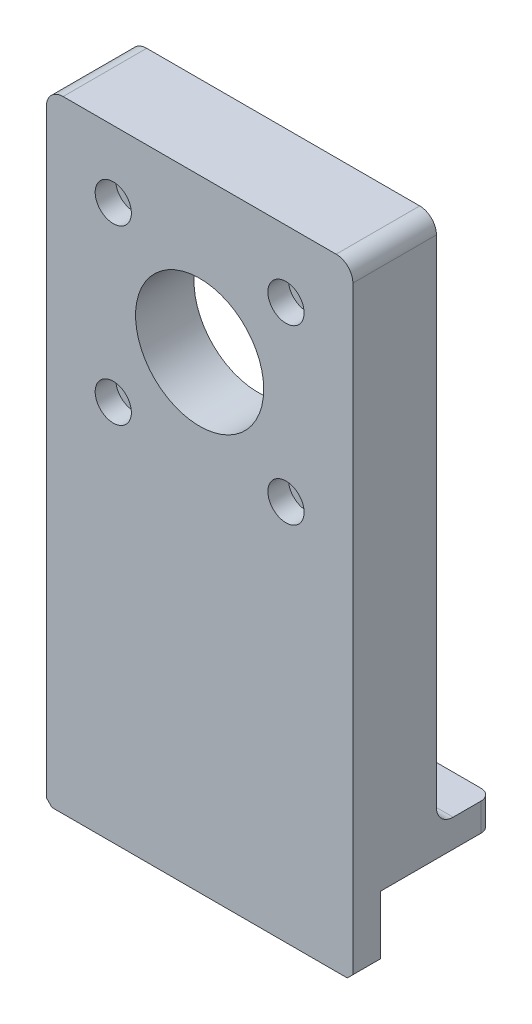
SolidWorks part; units mm, degrees
ref_plane "Přední rovina" through (0, 0, 0) normal (0, 0, 1) x (1, 0, 0)
ref_plane "Horní rovina" through (0, 0, 0) normal (0, 1, 0) x (1, 0, 0)
ref_plane "Pravá rovina" through (0, 0, 0) normal (1, 0, 0) x (0, 0, -1)
sketch "Skica2" plane through (0, 0, 0) normal (0, 0, 1) x (1, 0, 0)
  line L0 (-27.5, 24.5) -> (-27.5, -72.5)
  line L1 (27.5, 24.5) -> (27.5, -72.5)
  line L3 (27.5, -72.5) -> (-27.5, -72.5)
  line L7 (-24.5, 27.5) -> (24.5, 27.5)
  line L9 (-21.65, 21.65) -> (21.65, 21.65) construction
  line L12 (-21.65, 21.65) -> (-21.65, -21.65) construction
  line L13 (-21.65, -21.65) -> (21.65, -21.65) construction
  line L14 (21.65, 21.65) -> (21.65, -21.65) construction
  arc A3 (-24.5, 27.5) -> (-27.5, 24.5) centre (-24.5, 24.5) ccw
  arc A7 (27.5, 24.5) -> (24.5, 27.5) centre (24.5, 24.5) ccw
  circle A9 centre (0, 0) radius 11.5
  point P3 (0, 21.65)
  point P6 (-21.65, 0)
  point P8 (0, -72.5)
  dimension "D5" = 3
  dimension "D1" = 23
  dimension "D3" = 55
  dimension "D4" = 43.3
  dimension "D7" = 5.85
  dimension "D8" = 5.85
  dimension "D6" = 100
  dimension "D2" = 27.5
extrude "Přidat vysunutím1" add sketch "Skica2" against normal blind 15
sketch "Skica5" plane through (0, -72.5, 0) normal (0, -1, 0) x (1, 0, 0)
  line L0 (-27.5, -15) -> (-27.5, 0) construction
  line L1 (-27.5, -5) -> (27.5, -5)
  line L2 (-27.5, -5) -> (-27.5, 0)
  line L3 (-27.5, 0) -> (27.5, 0)
  line L4 (27.5, -5) -> (27.5, 0)
  line L5 (27.5, -15) -> (27.5, 0) construction
  dimension "D1" = 5
extrude "Přidat vysunutím4" add sketch "Skica5" along normal blind 11.5
chamfer "Zkosení1" distance 1 angle 45 2 edges at (27.5, -84, -2.5) (-27.5, -84, -2.5)
sketch "Skica6" plane through (0, 0, -15) normal (0, 0, -1) x (-1, 0, 0)
  line L0 (21.65, 21.65) -> (-21.65, 21.65) construction
  line L1 (-21.65, -21.65) -> (21.65, -21.65)
  line L2 (-21.65, -21.65) -> (-21.65, 21.65)
  line L3 (-21.65, 21.65) -> (21.65, 21.65)
  line L4 (21.65, -21.65) -> (21.65, 21.65)
  line L5 (-21.65, -21.65) -> (21.65, 21.65) construction
  line L6 (-21.65, 21.65) -> (21.65, -21.65) construction
  line L7 (-21.65, 21.65) -> (-21.65, -21.65) construction
  point P0 (0, 0)
extrude "Odebrat vysunutím1" cut sketch "Skica6" against normal blind 4.5
sketch "Skica7" plane through (0, 0, 0) normal (0, 0, 1) x (1, 0, 0)
  line L1 (-15.5, -15.5) -> (15.5, -15.5)
  line L2 (-15.5, -15.5) -> (-15.5, 15.5)
  line L3 (-15.5, 15.5) -> (15.5, 15.5)
  line L4 (15.5, -15.5) -> (15.5, 15.5)
  line L5 (-15.5, -15.5) -> (15.5, 15.5) construction
  line L6 (-15.5, 15.5) -> (15.5, -15.5) construction
  point P1 (15.5, 15.5)
  point P2 (-15.5, -15.5)
  point P3 (-15.5, 15.5)
  point P4 (15.5, -15.5)
  point P20 (0, 0)
  dimension "D1" = 31
hole_wizard "Válcové zahloubení pro M3 šrouby s vnitřním šestihranem1" positions "Skica7" profile "Skica8" counterbore size "M3" standard "ISO" end condition up to next
sketch "Skica8" plane through (15.5, 15.5, 0) normal (1, 0, 0) x (0, -1, 0)
  line L0 (0, 0) -> (0, 10.5)
  line L1 (0, 10.5) -> (1.75, 10.5)
  line L3 (1.75, 10.5) -> (1.75, 3.7)
  line L4 (1.75, 3.7) -> (3.25, 3.7)
  line L5 (3.25, 3.7) -> (3.25, 0)
  line L7 (3.25, 0) -> (0, 0)
  line L11 (0, -6.35) -> (0, 107.95) construction
  dimension "Průměr díry skrz" = 3.5
  dimension "Hloubka díry skrz" = 10.5
  dimension "Průměr válcového zahloubení" = 6.5
  dimension "Hloubka válcového zahloubení" = 3.7
sketch "Skica10" plane through (0, 0, -15) normal (0, 0, -1) x (-1, 0, 0)
  line L0 (27.5, 24.5) -> (27.5, -72.5) construction
  line L1 (-27.5, -72.5) -> (27.5, -72.5)
  line L2 (-27.5, -72.5) -> (-27.5, -67.5)
  line L3 (-27.5, -67.5) -> (27.5, -67.5)
  line L4 (27.5, -72.5) -> (27.5, -67.5)
  dimension "D1" = 5
extrude "Přidat vysunutím5" add sketch "Skica10" along normal blind 10
fillet "Zaoblit1" radius 2 2 edges at (-27.5, -70, -25) (27.5, -70, -25)
fillet "Zaoblit2" radius 3 1 edges at (0, -67.5, -15)
equation "\"D1@Skica2\"=22+1"
equation "\"D4@Skica2\"=42.3+1"
